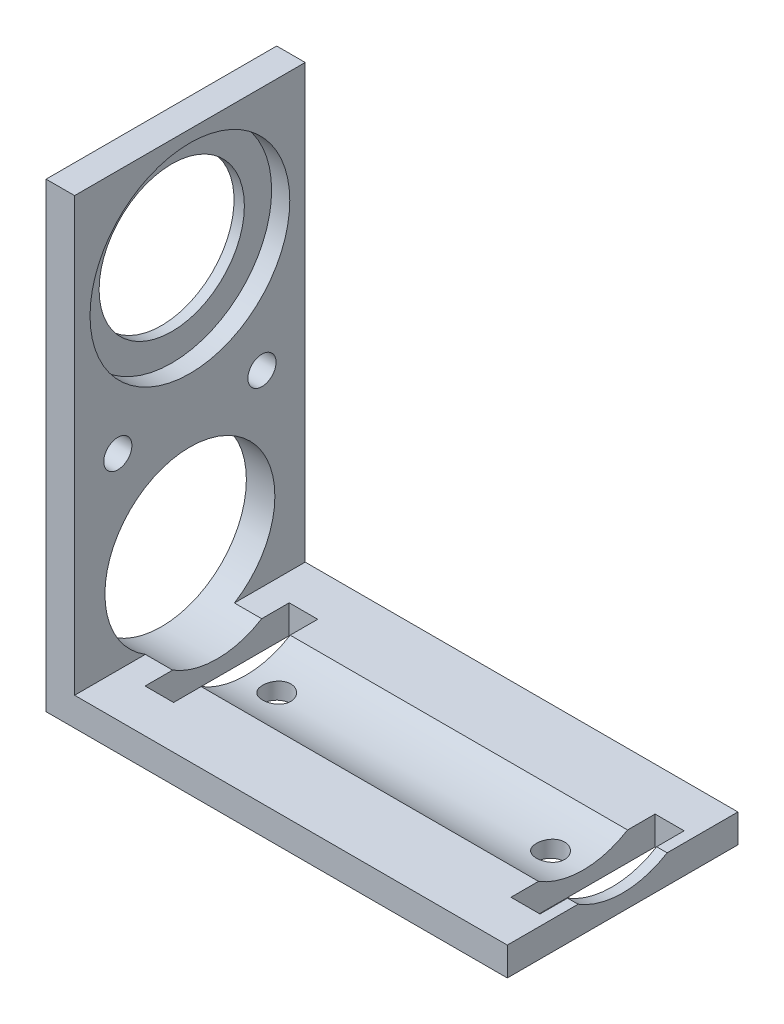
SolidWorks part; units mm, degrees
ref_plane "Front" through (0, 0, 0) normal (0, 0, 1) x (1, 0, 0)
ref_plane "Top" through (0, 0, 0) normal (0, 1, 0) x (1, 0, 0)
ref_plane "Right" through (0, 0, 0) normal (1, 0, 0) x (0, 0, -1)
sketch "Sketch1" plane through (0, 0, 0) normal (0, 0, 1) x (1, 0, 0)
  line L0 (0, 0) -> (50.8, 0)
  line L1 (50.8, 0) -> (50.8, 3.14)
  line L2 (50.8, 3.14) -> (3.14, 3.14)
  line L3 (3.14, 3.14) -> (3.14, 50.8)
  line L4 (3.14, 50.8) -> (0, 50.8)
  line L5 (0, 50.8) -> (0, 0)
extrude "Extrude1" add sketch "Sketch1" along normal blind 25.4
sketch "Sketch2" plane through (0, 0, 0) normal (-1, 0, 0) x (0, 0, 1)
  circle A0 centre (12.7, 11.1125) radius 9.36
  circle A1 centre (12.7, 38.4725) radius 8
  circle A2 centre (4.7625, 23.8125) radius 1.55
  circle A3 centre (20.6375, 23.8125) radius 1.55
extrude "Cut-Extrude1" cut sketch "Sketch2" against normal through all
sketch "Sketch3" plane through (3.14, 0, 0) normal (1, 0, 0) x (0, 0, -1)
  circle A0 centre (-12.7, 38.4725) radius 11
extrude "Cut-Extrude2" cut sketch "Sketch3" against normal blind 2
sketch "Sketch4" plane through (0, 0, 0) normal (0, -1, 0) x (1, 0, 0)
  line L0 (3.14, 4.7625) -> (0, 4.7625) construction
  line L1 (6.14, 4.7625) -> (9.28, 4.7625)
  line L2 (6.14, 4.7625) -> (6.14, 20.6375)
  line L3 (6.14, 20.6375) -> (9.28, 20.6375)
  line L4 (9.28, 4.7625) -> (9.28, 20.6375)
  line L5 (3.14, 20.6375) -> (0, 20.6375) construction
  line L6 (1.14, 12.7) -> (0, 12.7) construction
  line L7 (49.64, 20.6375) -> (46.44, 20.6375)
  line L8 (49.64, 20.6375) -> (49.64, 4.7625)
  line L9 (49.64, 4.7625) -> (46.44, 4.7625)
  line L10 (46.44, 20.6375) -> (46.44, 4.7625)
  circle A0 centre (12.7, 12.7) radius 1.55
  circle A1 centre (42.86, 12.7) radius 1.55
extrude "Cut-Extrude3" cut sketch "Sketch4" against normal through all
